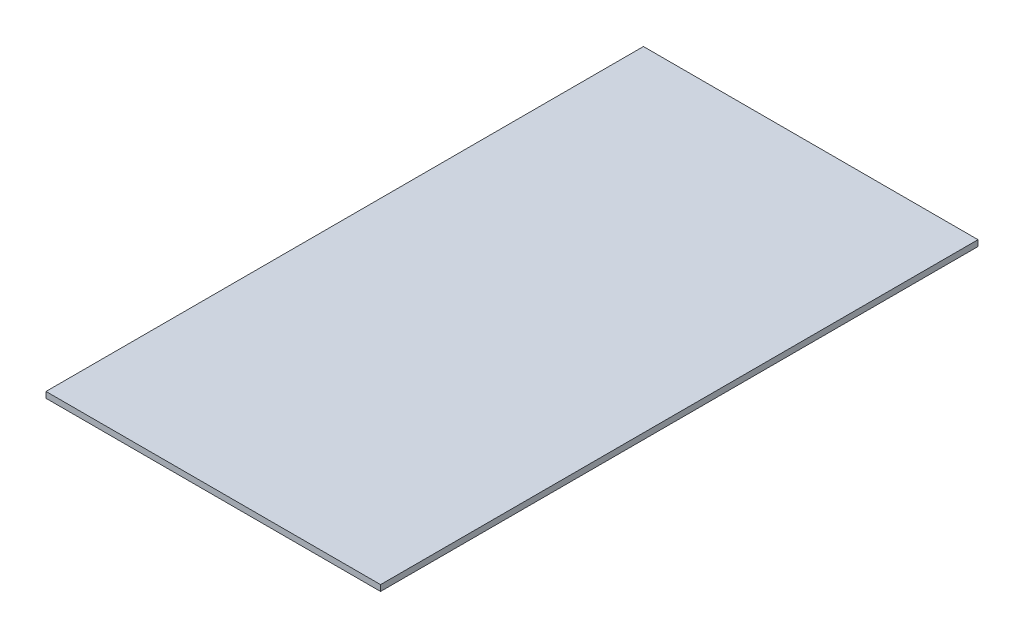
SolidWorks part; units mm, degrees
material "2024-T361"
ref_plane "Front Plane" through (0, 0, 0) normal (0, 0, 1) x (1, 0, 0)
ref_plane "Top Plane" through (0, 0, 0) normal (0, 1, 0) x (1, 0, 0)
ref_plane "Right Plane" through (0, 0, 0) normal (1, 0, 0) x (0, 0, -1)
sketch "Sketch1" plane through (0, 0, 0) normal (0, 1, 0) x (1, 0, 0)
  line L1 (-234.5784, 54.2328) -> (45.4216, 54.2328)
  line L2 (-234.5784, 54.2328) -> (-234.5784, -445.7672)
  line L3 (-234.5784, -445.7672) -> (45.4216, -445.7672)
  line L4 (45.4216, 54.2328) -> (45.4216, -445.7672)
  dimension "D1" = 280
  dimension "D2" = 500
extrude "Boss-Extrude1" add sketch "Sketch1" along normal blind 5 contours L4 L3 L2 L1
